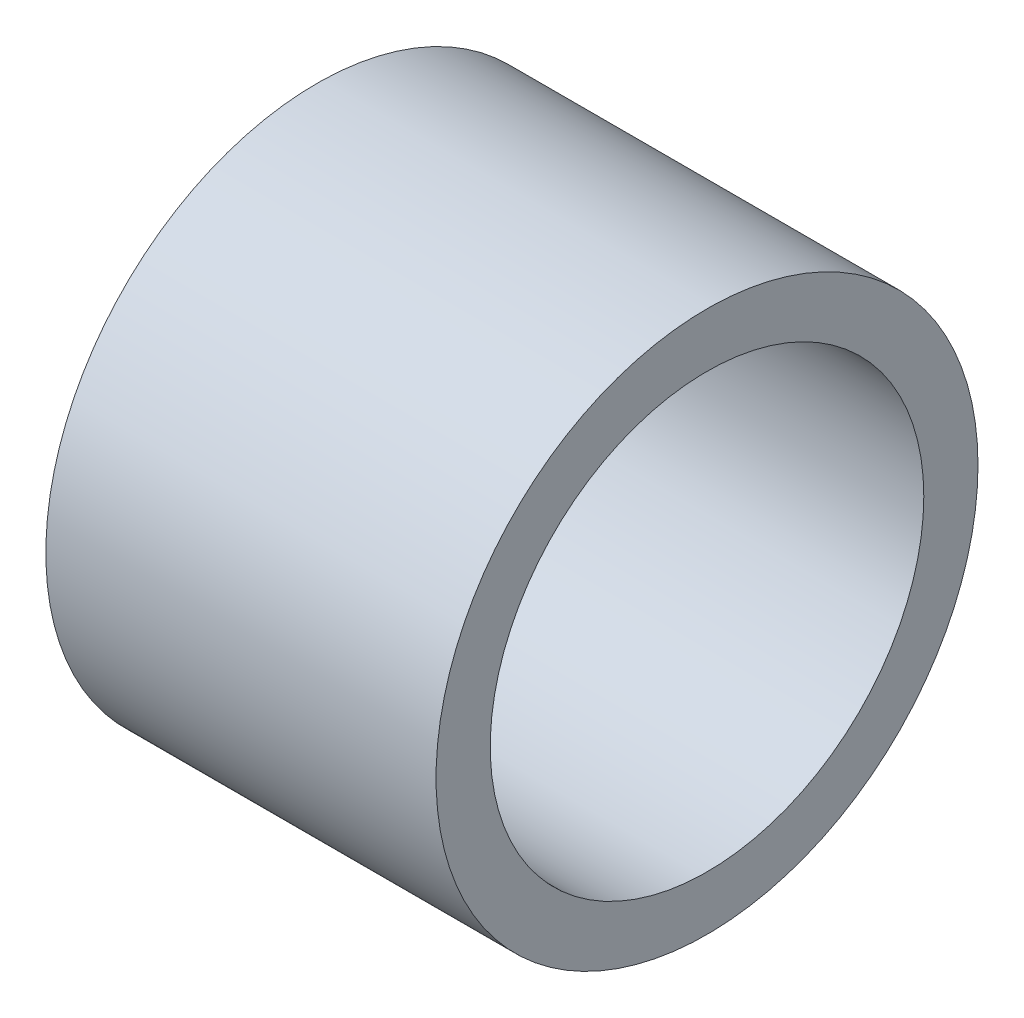
SolidWorks part; units mm, degrees
ref_plane "Front Plane" through (0, 0, 0) normal (1, 0, 0) x (0, 1, 0)
ref_plane "Top Plane" through (0, 0, 0) normal (0, 0, 1) x (0, 1, 0)
ref_plane "Right Plane" through (0, 0, 0) normal (0, 1, 0) x (-1, 0, 0)
sketch "Sketch2" plane through (0, 0, 0) normal (1, 0, 0) x (0, 1, 0)
  circle A0 centre (0, 0) radius 6.35
  circle A1 centre (0, 0) radius 7.9375
  dimension "D1" = 12.7
  dimension "D2" = 15.875
extrude "Boss-Extrude1" add sketch "Sketch2" along normal blind 11.43
